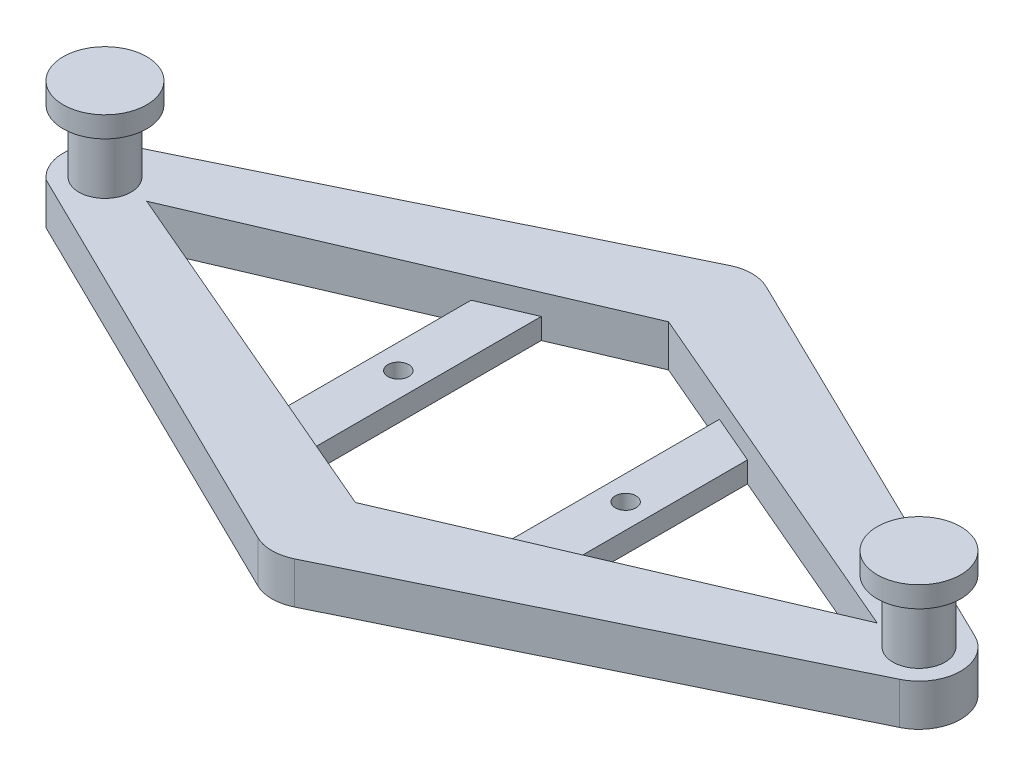
SolidWorks part; units mm, degrees
ref_plane "Front Plane" through (0, 0, 0) normal (0, 0, 1) x (1, 0, 0)
ref_plane "Top Plane" through (0, 0, 0) normal (0, 1, 0) x (1, 0, 0)
ref_plane "Right Plane" through (0, 0, 0) normal (1, 0, 0) x (0, 0, -1)
sketch "Base" plane through (0, 0, 0) normal (0, 1, 0) x (1, 0, 0)
  line L0 (0, 0) -> (49.53, 0)
  line L1 (0, 0) -> (-49.53, 0)
  line L2 (0, 0) -> (0, 24.13)
  line L3 (0, 0) -> (0, -24.13)
  line L4 (-44.45, 0) -> (0, 19.05)
  line L5 (0, 19.05) -> (44.45, 0)
  line L6 (44.45, 0) -> (0, -19.05)
  line L7 (0, -19.05) -> (-44.45, 0)
  line L8 (-51.7549, 4.5669) -> (-2.2249, 28.6969)
  line L9 (-52.8265, -3.8652) -> (-2.238, -28.6905)
  line L10 (2.2249, -28.6969) -> (51.7549, -4.5669)
  line L11 (51.7077, 4.5895) -> (2.2249, 28.6969)
  arc A0 (-51.7549, 4.5669) -> (-52.8265, -3.8652) centre (-49.53, 0) ccw
  arc A1 (2.2249, 28.6969) -> (-2.2249, 28.6969) centre (0, 24.13) ccw
  arc A2 (51.7549, -4.5669) -> (51.7077, 4.5895) centre (49.53, 0) ccw
  arc A3 (-2.238, -28.6905) -> (2.2249, -28.6969) centre (0, -24.13) ccw
  point P10 (0, 19.05)
  point P11 (-44.45, 0)
  point P12 (0, -19.05)
  point P13 (44.45, 0)
  point P27 (-51.7549, 4.5669)
  point P28 (-52.8265, -3.8652)
  point P29 (-2.238, -28.6905)
  point P30 (2.2249, -28.6969)
  point P31 (51.7549, -4.5669)
  point P32 (51.8018, 4.5437)
  point P33 (2.2249, 28.6969)
  point P34 (-2.2249, 28.6969)
sketch "Sketch4" plane through (0, 0, 0) normal (0, 1, 0) x (1, 0, 0)
  line L0 (-44.45, 0) -> (0, 19.05)
  line L1 (0, 19.05) -> (44.45, 0)
  line L2 (44.45, 0) -> (0, -19.05)
  line L3 (0, -19.05) -> (-44.45, 0)
  line L4 (-51.7549, 4.5669) -> (-2.2249, 28.6969)
  line L5 (-52.8265, -3.8652) -> (-2.238, -28.6905)
  line L6 (2.2249, -28.6969) -> (51.7549, -4.5669)
  line L7 (51.7077, 4.5895) -> (2.2249, 28.6969)
  arc A0 (-51.7549, 4.5669) -> (-52.8265, -3.8652) centre (-49.53, 0) ccw
  arc A1 (2.2249, 28.6969) -> (-2.2249, 28.6969) centre (0, 24.13) ccw
  arc A2 (51.7549, -4.5669) -> (51.7077, 4.5895) centre (49.53, 0) ccw
  arc A3 (-2.238, -28.6905) -> (2.2249, -28.6969) centre (0, -24.13) ccw
extrude "Boss-Extrude1" add sketch "Sketch4" along normal blind 5.08
sketch "Sketch5" plane through (0, 5.08, 0) normal (0, 1, 0) x (1, 0, 0)
  circle A0 centre (-49.53, 0) radius 3.175
  circle A1 centre (49.53, 0) radius 3.175
  point P6 (0, 0)
  point P7 (0, 0)
extrude "Boss-Extrude2" add sketch "Sketch5" along normal blind 7.62
sketch "Sketch8" plane through (0, 0, 0) normal (0, 1, 0) x (1, 0, 0)
  line L0 (-12.6059, 13.6475) -> (-12.6059, -13.6475)
  line L1 (-44.45, 0) -> (0, 19.05) construction
  line L2 (0, -19.05) -> (-44.45, 0) construction
  line L3 (-16.8237, 11.8398) -> (-16.8237, -11.8398)
  line L4 (0, 19.05) -> (0, -19.05)
  line L5 (12.6059, 13.6475) -> (12.6059, -13.6475)
  line L6 (16.8237, 11.8398) -> (16.8237, -11.8398)
  line L7 (-16.8237, 0) -> (-12.6059, 0)
  line L8 (12.6059, 0) -> (16.8237, 0)
  line L9 (-16.8237, 11.8398) -> (-12.6059, 13.6475)
  line L10 (-16.8237, -11.8398) -> (-12.6059, -13.6475)
  line L11 (12.6059, 13.6475) -> (16.8237, 11.8398)
  line L12 (12.6059, -13.6475) -> (16.8237, -11.8398)
  circle A0 centre (14.7148, 0) radius 1.27
  circle A1 centre (-14.7148, 0) radius 1.27
sketch "Sketch9" plane through (0, 0, 0) normal (0, 1, 0) x (1, 0, 0)
  line L0 (-10.839, 14.4047) -> (-10.839, -14.4047)
  line L1 (-16.8237, 11.8398) -> (-16.8237, -11.8398)
  line L4 (-16.8237, 11.8398) -> (-10.839, 14.4047)
  line L5 (-16.8237, -11.8398) -> (-10.839, -14.4047)
  line L8 (-44.45, 0) -> (0, 19.05) construction
  line L9 (0, -19.05) -> (-44.45, 0) construction
  line L10 (-16.8237, 0) -> (-10.839, 0)
  line L11 (0, 19.05) -> (0, -19.05)
  line L12 (16.8237, 11.8398) -> (10.839, 14.4047)
  line L13 (16.8237, -11.8398) -> (10.839, -14.4047)
  line L14 (16.8237, 11.8398) -> (16.8237, -11.8398)
  line L15 (10.839, 14.4047) -> (10.839, -14.4047)
  circle A2 centre (-13.8314, 0) radius 1.27
  circle A3 centre (13.8314, 0) radius 1.27
  point P8 (-13.8314, 13.1223)
  point P25 (13.8314, 13.1223)
sketch "Sketch11" plane through (0, 12.7, 0) normal (0, 1, 0) x (1, 0, 0)
  circle A0 centre (49.53, 0) radius 5.08
sketch "Sketch12" plane through (0, 12.7, 0) normal (0, 1, 0) x (1, 0, 0)
  circle A0 centre (49.53, 0) radius 5.08
extrude "Boss-Extrude4" add sketch "Sketch12" along normal blind 2.54
sketch "Sketch13" plane through (0, 12.7, 0) normal (0, 1, 0) x (1, 0, 0)
  circle A0 centre (-49.53, 0) radius 5.08
sketch "Sketch14" plane through (0, 12.7, 0) normal (0, 1, 0) x (1, 0, 0)
  circle A0 centre (-49.53, 0) radius 5.08
extrude "Boss-Extrude5" add sketch "Sketch14" along normal blind 2.54
sketch "Sketch15" plane through (0, 0, 0) normal (0, 1, 0) x (1, 0, 0)
  line L0 (-10.839, 14.4047) -> (-10.839, -14.4047)
  line L1 (-16.8237, 11.8398) -> (-16.8237, -11.8398)
  line L2 (-16.8237, 11.8398) -> (-10.839, 14.4047)
  line L3 (-16.8237, -11.8398) -> (-10.839, -14.4047)
  line L4 (16.8237, 11.8398) -> (10.839, 14.4047)
  line L5 (16.8237, -11.8398) -> (10.839, -14.4047)
  line L6 (16.8237, 11.8398) -> (16.8237, -11.8398)
  line L7 (10.839, 14.4047) -> (10.839, -14.4047)
  circle A0 centre (-13.8314, 0) radius 1.27
  circle A1 centre (13.8314, 0) radius 1.27
  point P4 (-10.839, 0)
  point P7 (-13.8314, 13.1223)
extrude "Boss-Extrude6" add sketch "Sketch15" along normal blind 2.54 separate body
